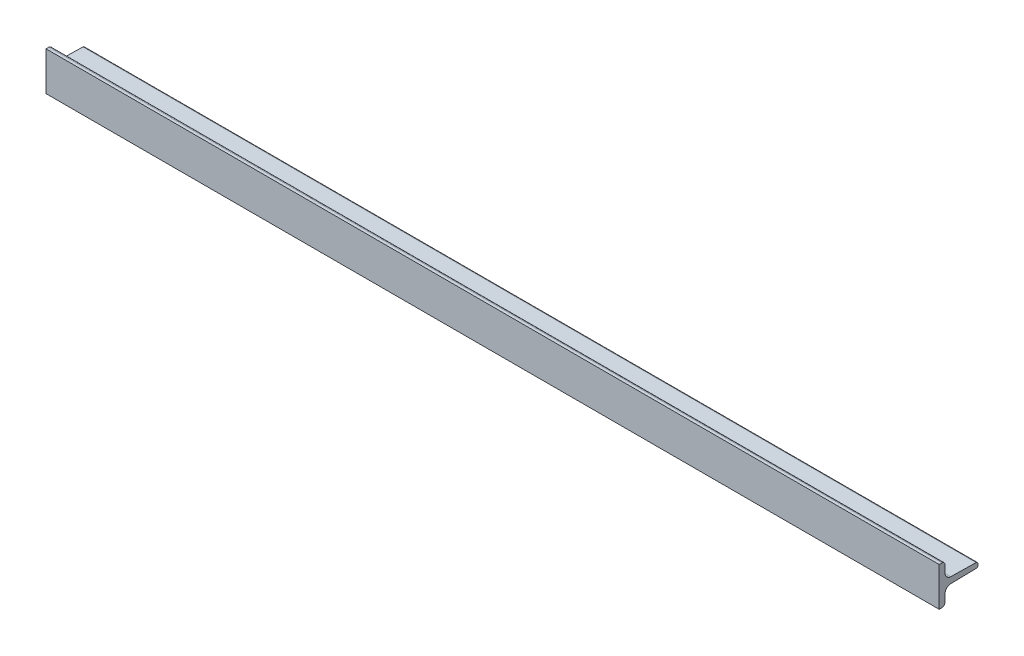
SolidWorks part; units mm, degrees
ref_plane "Front Plane" through (0, 0, 0) normal (0, 0, 1) x (1, 0, 0)
ref_plane "Top Plane" through (0, 0, 0) normal (0, 1, 0) x (1, 0, 0)
ref_plane "Right Plane" through (0, 0, 0) normal (1, 0, 0) x (0, 0, -1)
sketch "Sketch1" plane through (0, 0, 0) normal (0, 0, 1) x (1, 0, 0)
  line L0 (0, 0) -> (460, 0)
  point P4 (0, 0)
  dimension "D1" = 460
other "T section T 20 X 20(1)"
ref_plane "Plane1" through (0, 0, 0) normal (1, 0, 0) x (0, 1, 0)
sketch "Sketch12" plane through (0, 0, 0) normal (1, 0, 0) x (0, 1, 0)
  line L0 (-10, 20) -> (10, 20)
  line L2 (-1.3196, 0.98) -> (-1.581, 14.051)
  line L3 (-4.5204, 16.9904) -> (-8.53, 17.0706)
  line L5 (-10, 20) -> (-10, 18.5703)
  line L6 (10, 20) -> (10, 18.5703)
  line L7 (8.53, 17.0706) -> (4.5204, 16.9904)
  line L8 (1.581, 14.051) -> (1.3196, 0.98)
  line L9 (-5, 17) -> (5, 17) construction
  line L10 (0, 20) -> (0, 0) construction
  line L12 (-0.3198, 0) -> (0.3198, 0)
  arc A0 (-8.53, 17.0706) -> (-10, 18.5703) centre (-8.5, 18.5703) cw
  arc A1 (8.53, 17.0706) -> (10, 18.5703) centre (8.5, 18.5703) ccw
  arc A2 (-1.581, 14.051) -> (-4.5204, 16.9904) centre (-4.5804, 13.991) ccw
  arc A3 (4.5204, 16.9904) -> (1.581, 14.051) centre (4.5804, 13.991) ccw
  arc A4 (-0.3198, 0) -> (-1.3196, 0.98) centre (-0.3198, 1) cw
  arc A5 (1.3196, 0.98) -> (0.3198, 0) centre (0.3198, 1) cw
  point P16 (10, 17.1)
  point P24 (-1.3, 0)
  point P27 (1.3, 0)
  point P28 (0, 0)
  dimension "D2" = 1.146
  dimension "R2" = 1.5
  dimension "R1" = 3
  dimension "R3" = 1
  dimension "D1" = 1.146
  dimension "D3" = 2.9
  dimension "BF" = 20
  dimension "DEPTH" = 20
  dimension "TF" = 3
  dimension "D4" = 2.5999
  dimension "D5" = 1.146
